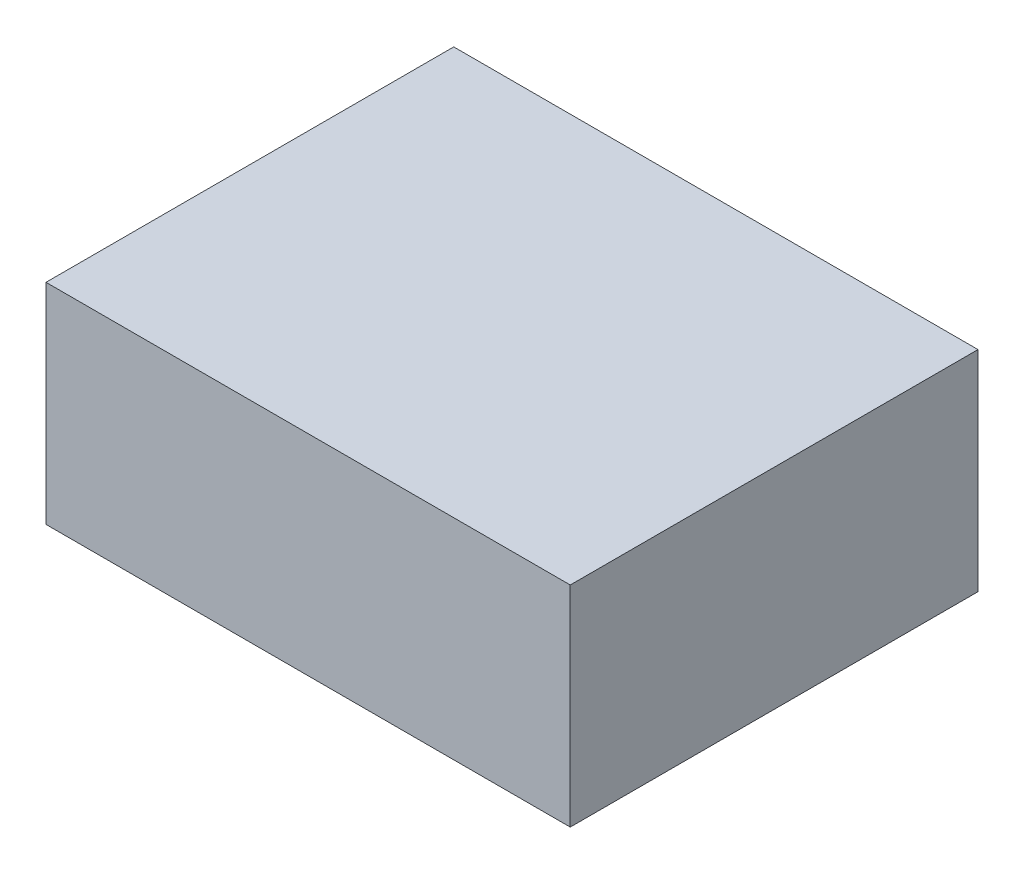
SolidWorks part; units mm, degrees
ref_plane "Front Plane" through (0, 0, 0) normal (0, 0, 1) x (1, 0, 0)
ref_plane "Top Plane" through (0, 0, 0) normal (0, 1, 0) x (1, 0, 0)
ref_plane "Right Plane" through (0, 0, 0) normal (1, 0, 0) x (0, 0, -1)
sketch "Sketch1" plane through (0, 0, 0) normal (0, 1, 0) x (1, 0, 0)
  line L1 (-22.5, -17.5) -> (22.5, -17.5)
  line L2 (-22.5, -17.5) -> (-22.5, 17.5)
  line L3 (-22.5, 17.5) -> (22.5, 17.5)
  line L4 (22.5, -17.5) -> (22.5, 17.5)
  line L5 (-22.5, -17.5) -> (22.5, 17.5) construction
  line L6 (-22.5, 17.5) -> (22.5, -17.5) construction
  point P0 (0, 0)
  dimension "D1" = 35
  dimension "D2" = 45
extrude "Boss-Extrude1" add sketch "Sketch1" along normal blind 18
